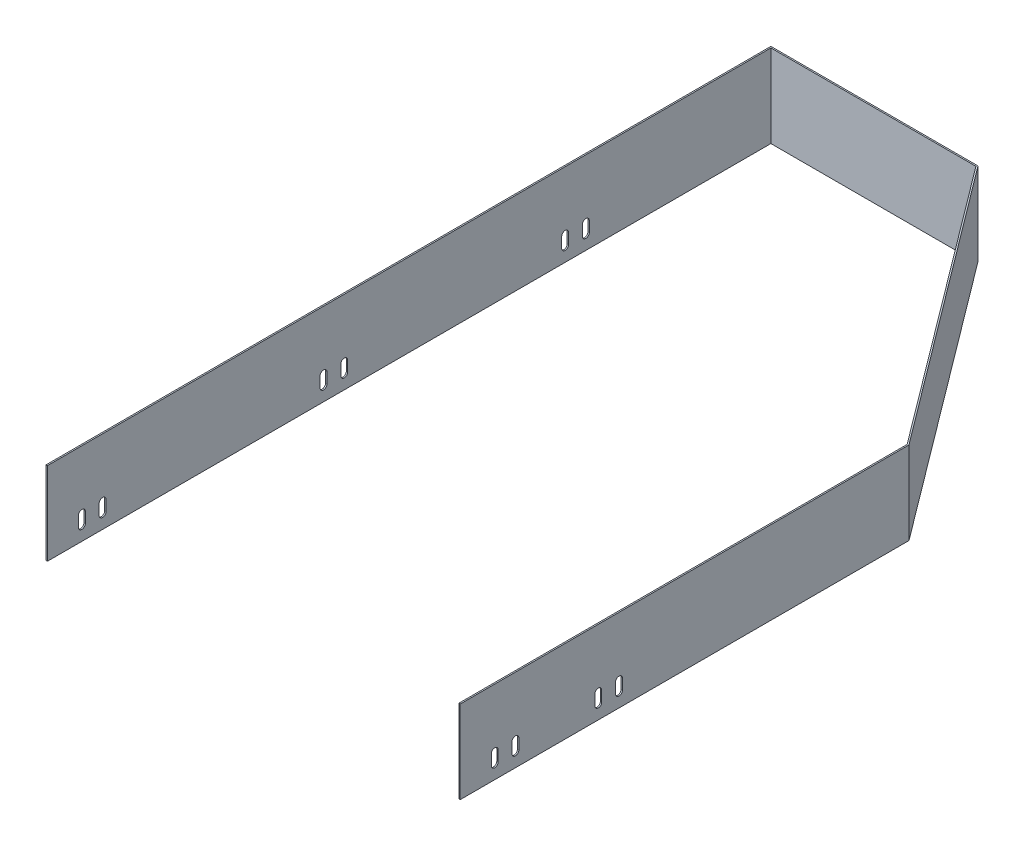
SolidWorks part; units mm, degrees
material "Alloy Steel (SS)"
ref_plane "Front Plane" through (0, 0, 0) normal (0, 0, 1) x (1, 0, 0)
ref_plane "Top Plane" through (0, 0, 0) normal (0, 1, 0) x (1, 0, 0)
ref_plane "Right Plane" through (0, 0, 0) normal (1, 0, 0) x (0, 0, -1)
sketch "Sketch1" plane through (0, 0, 0) normal (0, 1, 0) x (1, 0, 0)
  line L0 (0, 0) -> (0, 1050)
  line L1 (0, 1050) -> (300, 1050)
  line L2 (300, 1050) -> (600, 650)
  line L3 (600, 650) -> (600, 0)
  line L5 (2, 0) -> (2, 1048)
  line L6 (2, 1048) -> (299, 1048)
  line L7 (299, 1048) -> (598, 649.3333)
  line L8 (598, 649.3333) -> (598, 0)
  line L9 (0, 0) -> (2, 0)
  line L10 (598, 0) -> (600, 0)
  dimension "D1" = 1050
  dimension "D2" = 650
  dimension "D3" = 300
  dimension "D5" = 600
  dimension "D4" = 2
extrude "Boss-Extrude1" add sketch "Sketch1" along normal blind 120
sketch "Sketch2" plane through (0, 0, 0) normal (-1, 0, 0) x (0, 0, 1)
  line L0 (-1050, 120) -> (0, 120) construction
  circle A0 centre (-5, 121) radius 1
  circle A1 centre (-20, 121) radius 1
  circle A2 centre (-35, 121) radius 1
  circle A3 centre (-50, 121) radius 1
  circle A4 centre (-65, 121) radius 1
  circle A5 centre (-80, 121) radius 1
  circle A6 centre (-95, 121) radius 1
  circle A7 centre (-110, 121) radius 1
  circle A8 centre (-125, 121) radius 1
  circle A9 centre (-140, 121) radius 1
  circle A10 centre (-155, 121) radius 1
  circle A11 centre (-170, 121) radius 1
  circle A12 centre (-185, 121) radius 1
  circle A13 centre (-200, 121) radius 1
  circle A14 centre (-215, 121) radius 1
  circle A15 centre (-230, 121) radius 1
  circle A16 centre (-245, 121) radius 1
  circle A17 centre (-260, 121) radius 1
  circle A18 centre (-275, 121) radius 1
  circle A19 centre (-290, 121) radius 1
  circle A20 centre (-305, 121) radius 1
  circle A21 centre (-320, 121) radius 1
  circle A22 centre (-335, 121) radius 1
  circle A23 centre (-350, 121) radius 1
  circle A24 centre (-365, 121) radius 1
  circle A25 centre (-380, 121) radius 1
  circle A26 centre (-395, 121) radius 1
  circle A27 centre (-410, 121) radius 1
  circle A28 centre (-425, 121) radius 1
  circle A29 centre (-440, 121) radius 1
  circle A30 centre (-455, 121) radius 1
  circle A31 centre (-470, 121) radius 1
  circle A32 centre (-485, 121) radius 1
  circle A33 centre (-500, 121) radius 1
  circle A34 centre (-515, 121) radius 1
  circle A35 centre (-530, 121) radius 1
  circle A36 centre (-545, 121) radius 1
  circle A37 centre (-560, 121) radius 1
  circle A38 centre (-575, 121) radius 1
  circle A39 centre (-590, 121) radius 1
  circle A40 centre (-605, 121) radius 1
  circle A41 centre (-620, 121) radius 1
  circle A42 centre (-635, 121) radius 1
  circle A43 centre (-650, 121) radius 1
  circle A44 centre (-665, 121) radius 1
  circle A45 centre (-680, 121) radius 1
  circle A46 centre (-695, 121) radius 1
  circle A47 centre (-710, 121) radius 1
  circle A48 centre (-725, 121) radius 1
  circle A49 centre (-740, 121) radius 1
  circle A50 centre (-755, 121) radius 1
  circle A51 centre (-770, 121) radius 1
  circle A52 centre (-785, 121) radius 1
  circle A53 centre (-800, 121) radius 1
  circle A54 centre (-815, 121) radius 1
  circle A55 centre (-830, 121) radius 1
  circle A56 centre (-845, 121) radius 1
  circle A57 centre (-860, 121) radius 1
  circle A58 centre (-875, 121) radius 1
  circle A59 centre (-890, 121) radius 1
  circle A60 centre (-905, 121) radius 1
  circle A61 centre (-920, 121) radius 1
  circle A62 centre (-935, 121) radius 1
  circle A63 centre (-950, 121) radius 1
  circle A64 centre (-965, 121) radius 1
  circle A65 centre (-980, 121) radius 1
  circle A66 centre (-995, 121) radius 1
  circle A67 centre (-1010, 121) radius 1
  circle A68 centre (-1025, 121) radius 1
  circle A69 centre (-1040, 121) radius 1
  dimension "D1" = 2
  dimension "D2" = 5
  dimension "D3" = 70
extrude "Boss-Extrude2" [suppressed] add sketch "Sketch2" against normal up to surface (600 mm away) separate body
sketch "Sketch4" plane through (0, 0, -1050) normal (0, 0, -1) x (-1, 0, 0)
  line L0 (-300, 120) -> (0, 120) construction
  circle A0 centre (-5, 121) radius 1
  circle A1 centre (-20, 121) radius 1
  circle A2 centre (-35, 121) radius 1
  circle A3 centre (-50, 121) radius 1
  circle A4 centre (-65, 121) radius 1
  circle A5 centre (-80, 121) radius 1
  circle A6 centre (-95, 121) radius 1
  circle A7 centre (-110, 121) radius 1
  circle A8 centre (-125, 121) radius 1
  circle A9 centre (-140, 121) radius 1
  circle A10 centre (-155, 121) radius 1
  circle A11 centre (-170, 121) radius 1
  circle A12 centre (-185, 121) radius 1
  circle A13 centre (-200, 121) radius 1
  circle A14 centre (-215, 121) radius 1
  circle A15 centre (-230, 121) radius 1
  circle A16 centre (-245, 121) radius 1
  circle A17 centre (-260, 121) radius 1
  circle A18 centre (-275, 121) radius 1
  circle A19 centre (-290, 121) radius 1
  circle A20 centre (-305, 121) radius 1
  circle A21 centre (-320, 121) radius 1
  circle A22 centre (-335, 121) radius 1
  circle A23 centre (-350, 121) radius 1
  circle A24 centre (-365, 121) radius 1
  circle A25 centre (-380, 121) radius 1
  circle A26 centre (-395, 121) radius 1
  circle A27 centre (-410, 121) radius 1
  circle A28 centre (-425, 121) radius 1
  circle A29 centre (-440, 121) radius 1
  circle A30 centre (-455, 121) radius 1
  circle A31 centre (-470, 121) radius 1
  circle A32 centre (-485, 121) radius 1
  circle A33 centre (-500, 121) radius 1
  circle A34 centre (-515, 121) radius 1
  circle A35 centre (-530, 121) radius 1
  circle A36 centre (-545, 121) radius 1
  circle A45 centre (-560, 121) radius 1
  circle A46 centre (-575, 121) radius 1
  circle A47 centre (-590, 121) radius 1
  dimension "D1" = 2
  dimension "D2" = 5
  dimension "D3" = 40
extrude "Boss-Extrude3" [suppressed] add sketch "Sketch4" against normal blind 1045
sketch "Sketch6" plane through (0, 120, 0) normal (0, 1, 0) x (1, 0, 0)
  line L0 (300, 1050) -> (600, 650)
  line L1 (600, 650) -> (771.9668, 650)
  line L2 (771.9668, 650) -> (771.9668, 1225.1172)
  line L3 (771.9668, 1225.1172) -> (300, 1225.1172)
  line L4 (300, 1225.1172) -> (300, 1050)
extrude "Cut-Extrude1" [suppressed] cut sketch "Sketch6" against normal mid plane 80
sketch "Sketch7" plane through (600, 0, 0) normal (1, 0, 0) x (0, 0, -1)
  line L0 (50, 20) -> (50, 35) construction
  line L1 (45, 20) -> (45, 35)
  line L2 (55, 20) -> (55, 35)
  line L5 (80, 20) -> (80, 35) construction
  line L6 (75, 20) -> (75, 35)
  line L7 (85, 20) -> (85, 35)
  line L8 (200, 20) -> (200, 35) construction
  line L11 (195, 20) -> (195, 35)
  line L14 (205, 20) -> (205, 35)
  line L15 (230, 20) -> (230, 35) construction
  line L16 (225, 20) -> (225, 35)
  line L17 (235, 20) -> (235, 35)
  arc A0 (45, 20) -> (55, 20) centre (50, 20) ccw
  arc A1 (55, 35) -> (45, 35) centre (50, 35) ccw
  arc A2 (75, 20) -> (85, 20) centre (80, 20) ccw
  arc A3 (85, 35) -> (75, 35) centre (80, 35) ccw
  arc A8 (195, 20) -> (205, 20) centre (200, 20) ccw
  arc A9 (205, 35) -> (195, 35) centre (200, 35) ccw
  arc A10 (225, 20) -> (235, 20) centre (230, 20) ccw
  arc A11 (235, 35) -> (225, 35) centre (230, 35) ccw
  point P2 (50, 27.5)
  point P7 (55, 27.5)
  point P13 (80, 27.5)
  point P20 (200, 27.5)
  point P27 (230, 27.5)
  dimension "D1" = 10
  dimension "D2" = 15
  dimension "D3" = 50
  dimension "D4" = 27.5
  dimension "D5" = 2
  dimension "D6" = 2
extrude "Cut-Extrude2" cut sketch "Sketch7" against normal up to surface (2 mm away) up to face at (598, 60, -324.6667)
sketch "Sketch8" plane through (0, 0, 0) normal (-1, 0, 0) x (0, 0, 1)
  line L0 (-50, 35) -> (-50, 20) construction
  line L1 (-45, 35) -> (-45, 20)
  line L2 (-55, 35) -> (-55, 20)
  line L3 (-80, 35) -> (-80, 20) construction
  line L4 (-75, 35) -> (-75, 20)
  line L5 (-85, 35) -> (-85, 20)
  line L6 (-400, 35) -> (-400, 20) construction
  line L9 (-395, 35) -> (-395, 20)
  line L12 (-405, 35) -> (-405, 20)
  line L15 (-430, 35) -> (-430, 20) construction
  line L18 (-425, 35) -> (-425, 20)
  line L19 (-435, 35) -> (-435, 20)
  line L20 (-750, 35) -> (-750, 20) construction
  line L21 (-745, 35) -> (-745, 20)
  line L22 (-755, 35) -> (-755, 20)
  line L23 (-780, 35) -> (-780, 20) construction
  line L24 (-775, 35) -> (-775, 20)
  line L25 (-785, 35) -> (-785, 20)
  arc A0 (-45, 35) -> (-55, 35) centre (-50, 35) ccw
  arc A1 (-55, 20) -> (-45, 20) centre (-50, 20) ccw
  arc A2 (-75, 35) -> (-85, 35) centre (-80, 35) ccw
  arc A3 (-85, 20) -> (-75, 20) centre (-80, 20) ccw
  arc A12 (-395, 35) -> (-405, 35) centre (-400, 35) ccw
  arc A13 (-405, 20) -> (-395, 20) centre (-400, 20) ccw
  arc A14 (-425, 35) -> (-435, 35) centre (-430, 35) ccw
  arc A15 (-435, 20) -> (-425, 20) centre (-430, 20) ccw
  arc A16 (-745, 35) -> (-755, 35) centre (-750, 35) ccw
  arc A17 (-755, 20) -> (-745, 20) centre (-750, 20) ccw
  arc A18 (-775, 35) -> (-785, 35) centre (-780, 35) ccw
  arc A19 (-785, 20) -> (-775, 20) centre (-780, 20) ccw
  point P2 (-50, 27.5)
  point P10 (-80, 27.5)
  point P20 (-400, 27.5)
  point P27 (-430, 27.5)
  point P34 (-750, 27.5)
  point P41 (-780, 27.5)
  dimension "D2" = 5
  dimension "D1" = 15
  dimension "D4" = 27.5
  dimension "D5" = 50
  dimension "D3" = 2
extrude "Cut-Extrude3" cut sketch "Sketch8" against normal up to surface (2 mm away) up to face at (2, 60, -524)
